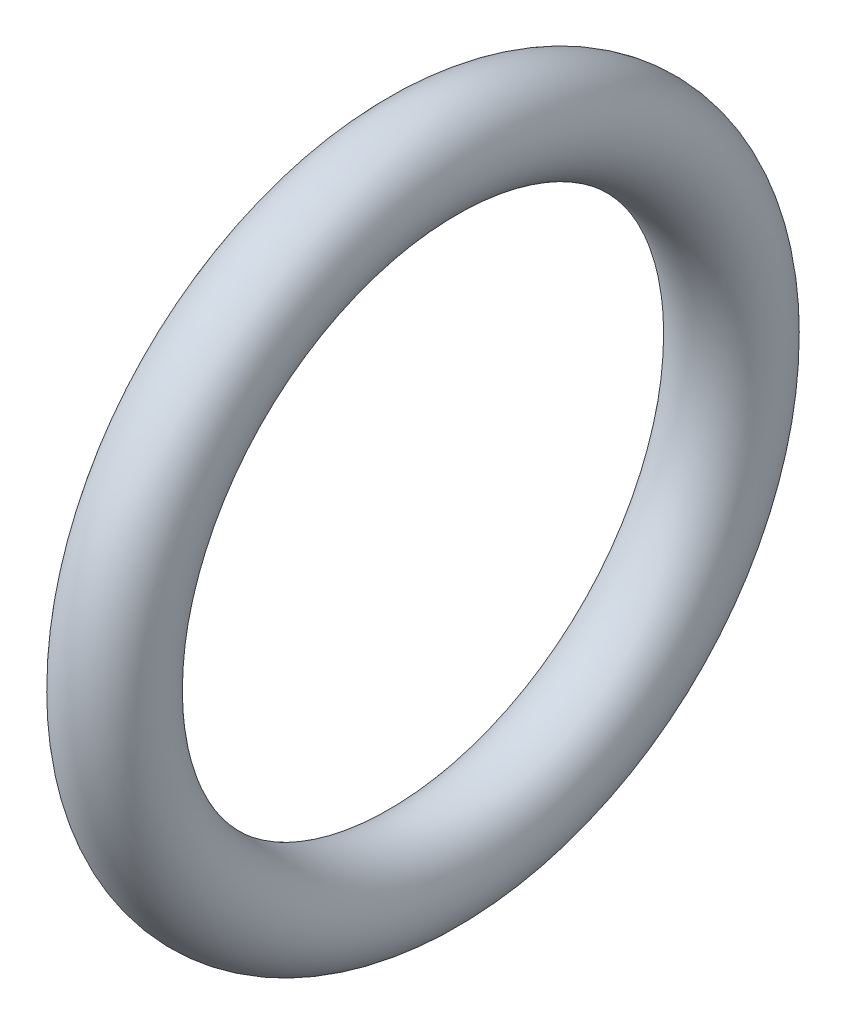
SolidWorks part; units mm, degrees
ref_plane "Front Plane" through (0, 0, 0) normal (0, 0, 1) x (1, 0, 0)
ref_plane "Top Plane" through (0, 0, 0) normal (0, 1, 0) x (1, 0, 0)
ref_plane "Right Plane" through (0, 0, 0) normal (1, 0, 0) x (0, 0, -1)
sketch "Sketch1" plane through (0, 0, 0) normal (0, 0, 1) x (1, 0, 0)
  line L0 (0, 0) -> (0, 22.781) construction
  circle A0 centre (0, 9) radius 1.4
  dimension "D1" = 2.8
  dimension "D2" = 9
ref_axis "Axis1" through (1.54, 0, 0) along (-1, 0, 0)
revolve "Revolve1" add sketch "Sketch1" angle 360 about axis through (1.54, 0, 0) along (-1, 0, 0)
